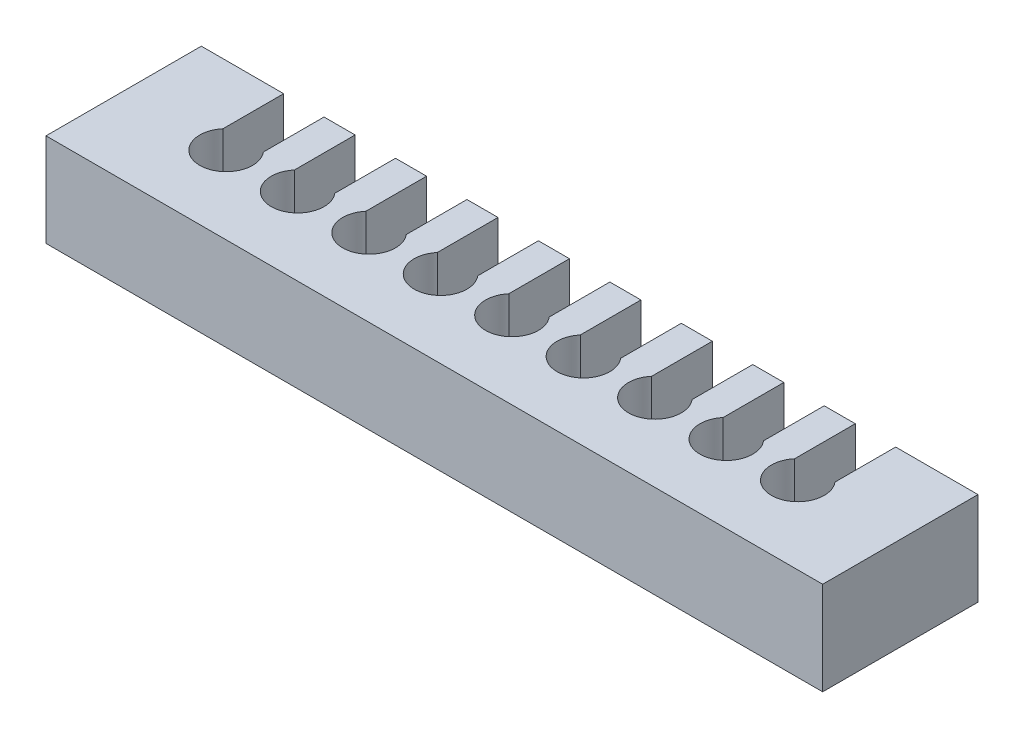
SolidWorks part; units mm, degrees
ref_plane "Alzado" through (0, 0, 0) normal (0, 0, 1) x (1, 0, 0)
ref_plane "Planta" through (0, 0, 0) normal (0, 1, 0) x (1, 0, 0)
ref_plane "Vista lateral" through (0, 0, 0) normal (1, 0, 0) x (0, 0, -1)
sketch "Croquis1" plane through (0, 0, 0) normal (0, 1, 0) x (1, 0, 0)
  line L1 (-12.5, -2.5) -> (12.5, -2.5)
  line L2 (-12.5, -2.5) -> (-12.5, 2.5)
  line L3 (-12.5, 2.5) -> (12.5, 2.5)
  line L4 (12.5, -2.5) -> (12.5, 2.5)
  line L5 (-12.5, -2.5) -> (12.5, 2.5) construction
  line L6 (-12.5, 2.5) -> (12.5, -2.5) construction
  point P0 (0, 0)
extrude "Saliente-Extruir1" add sketch "Croquis1" along normal blind 3
sketch "Croquis2" plane through (0, 3, 0) normal (0, 1, 0) x (1, 0, 0)
  line L0 (0, 0) -> (0, 2.5) construction
  line L1 (0, 2.5) -> (0.65, 2.5)
  line L2 (12.5, 2.5) -> (-12.5, 2.5) construction
  line L3 (0, 2.5) -> (-0.65, 2.5)
  line L4 (-0.65, 2.5) -> (-0.65, 0.5477)
  line L5 (0.65, 2.5) -> (0.65, 0.5477)
  circle A0 centre (0, 0) radius 0.85
extrude "Cortar-Extruir6" cut sketch "Croquis2" against normal blind 3
pattern_linear "MatrizL4" count 5 spacing 2.3 along (1, 0, 0) of "Cortar-Extruir6"
mirror "Simetría3" about plane through (0, 0, 0) normal (1, 0, 0) of "MatrizL4"
